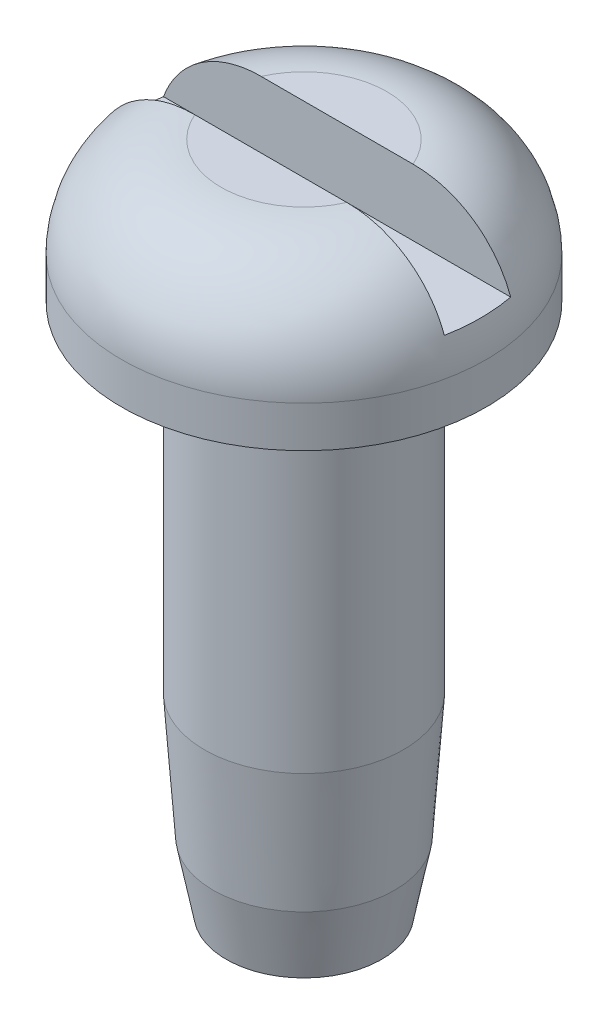
SolidWorks part; units mm, degrees
ref_plane "Спереди" through (0, 0, 0) normal (0, 0, 1) x (1, 0, 0)
ref_plane "Сверху" through (0, 0, 0) normal (0, 1, 0) x (1, 0, 0)
ref_plane "Справа" through (0, 0, 0) normal (1, 0, 0) x (0, 0, -1)
sketch "Эскиз1" plane through (0, 0, 0) normal (0, 0, 1) x (1, 0, 0)
  line L0 (0, 0) -> (0, 10.12)
  line L1 (0, 10.12) -> (1.25, 10.12)
  line L2 (2.75, 8.62) -> (2.75, 8)
  line L3 (2.75, 8) -> (1.5, 8)
  line L4 (1.5, 8) -> (1.5, 2.9)
  line L5 (1.5, 2.9) -> (1.3671, 1)
  line L6 (1.1728, 0) -> (0, 0)
  line L7 (1.3671, 1) -> (1.1728, 0)
  arc A0 (1.25, 10.12) -> (2.75, 8.62) centre (1.25, 8.62) cw
  dimension "D5" = 1.5
  dimension "D1" = 1.5
  dimension "D2" = 2.12
  dimension "D3" = 8
  dimension "D4" = 2.75
  dimension "D6" = 2.9
  dimension "D7" = 4
  dimension "D8" = 7
  dimension "D9" = 1
revolve "Повернуть1" add sketch "Эскиз1" angle 360 about L0
sketch "Эскиз2" plane through (0, 0, 0) normal (1, 0, 0) x (0, 0, -1)
  line L0 (0, 9.12) -> (0, 0) construction
  line L1 (-0.5, 10.12) -> (0.5, 10.12)
  line L2 (-0.5, 10.12) -> (-0.5, 9.12)
  line L3 (-0.5, 9.12) -> (0.5, 9.12)
  line L4 (0.5, 10.12) -> (0.5, 9.12)
  line L5 (-1.1728, 0) -> (1.1728, 0) construction
  line L6 (1.25, 10.12) -> (-1.25, 10.12) construction
  dimension "D1" = 1
  dimension "D2" = 1
extrude "Вырез-Вытянуть1" cut sketch "Эскиз2" against normal mid plane 10
